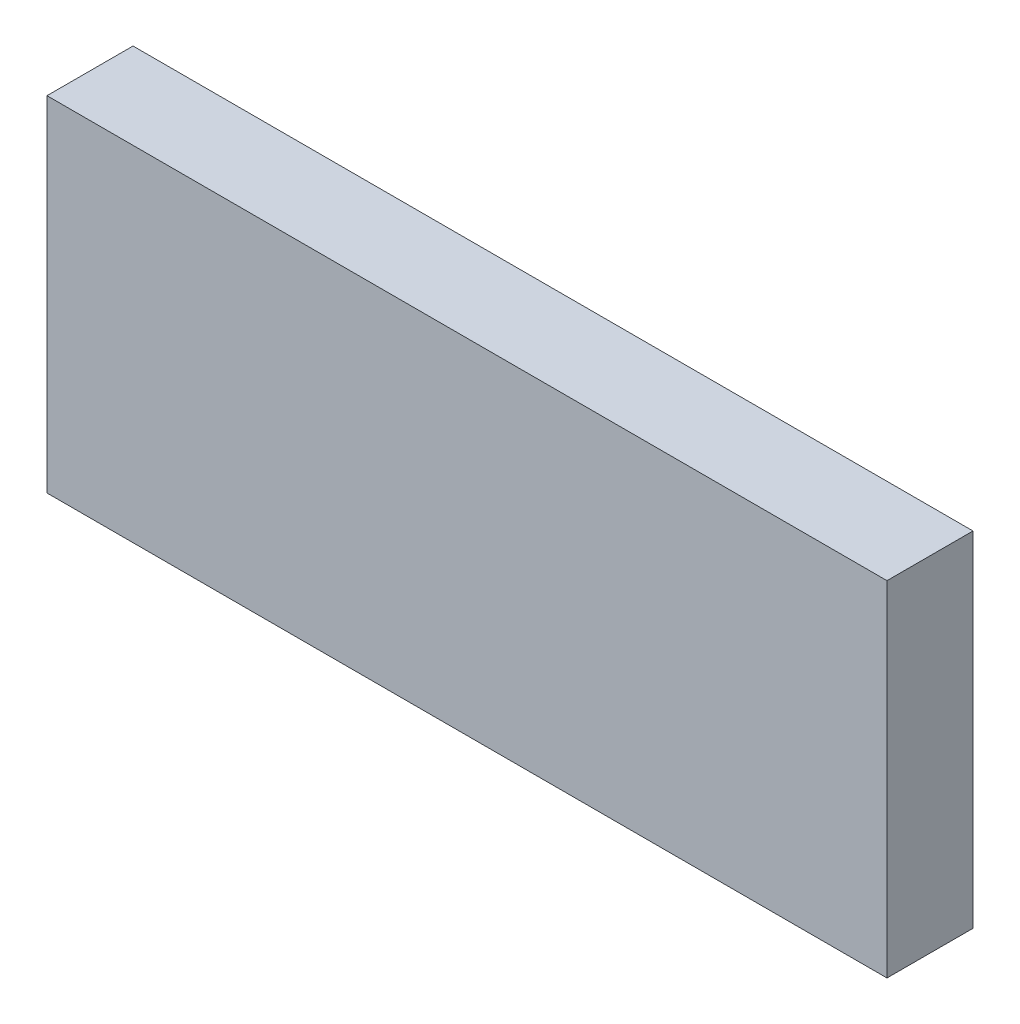
SolidWorks part; units mm, degrees
ref_plane "Plano frontal" through (0, 0, 0) normal (0, 0, 1) x (1, 0, 0)
ref_plane "Plano superior" through (0, 0, 0) normal (0, 1, 0) x (1, 0, 0)
ref_plane "Plano direito" through (0, 0, 0) normal (1, 0, 0) x (0, 0, -1)
sketch "Esboço1" plane through (0, 0, 0) normal (0, 0, 1) x (1, 0, 0)
  line L1 (0, 0) -> (62, 0)
  line L2 (0, 0) -> (0, 25.4)
  line L3 (0, 25.4) -> (62, 25.4)
  line L4 (62, 0) -> (62, 25.4)
  dimension "D1" = 62
  dimension "D2" = 25.4
extrude "Ressalto-extrusão1" add sketch "Esboço1" along normal blind 6.35
